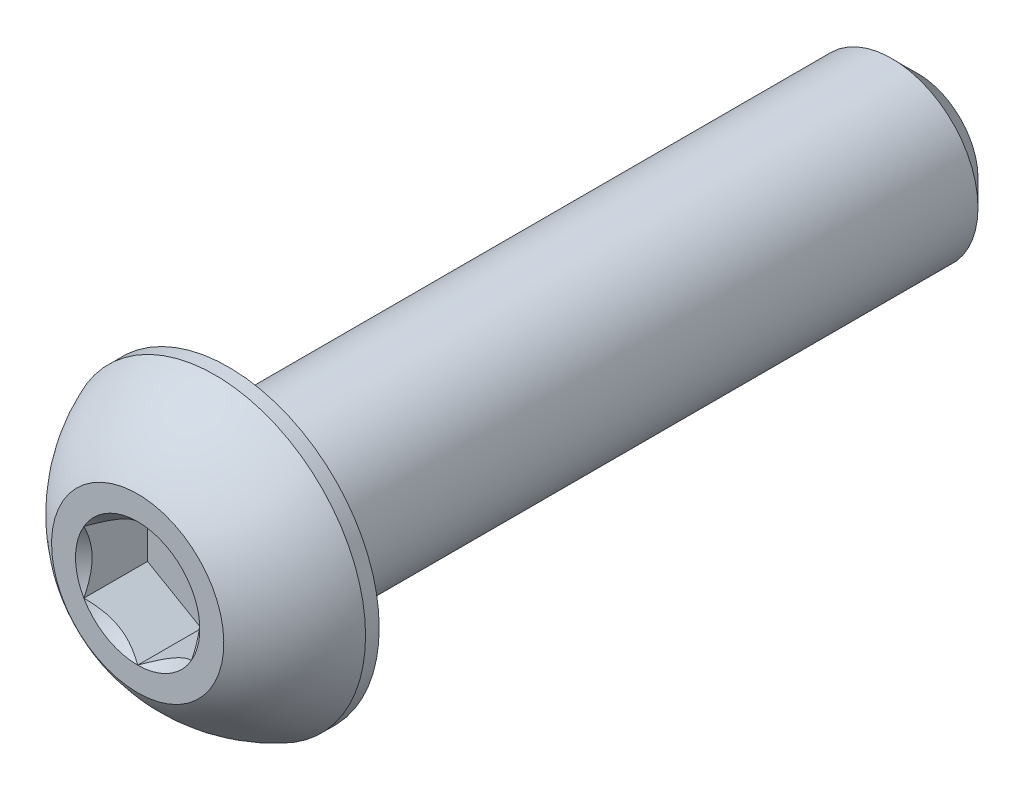
SolidWorks part; units mm, degrees
ref_plane "Front" through (0, 0, 0) normal (0, 0, 1) x (1, 0, 0)
ref_plane "Top" through (0, 0, 0) normal (0, 1, 0) x (1, 0, 0)
ref_plane "Right" through (0, 0, 0) normal (1, 0, 0) x (0, 0, -1)
sketch "Sketch1" plane through (0, 0, 0) normal (1, 0, 0) x (0, 0, -1)
  line L2 (3.3528, 3.175) -> (28.7528, 3.175)
  line L3 (28.7528, 3.175) -> (28.7528, 0)
  line L4 (28.7528, 0) -> (3.3528, 0)
  line L6 (2.8499, 5.5499) -> (3.3528, 5.5499) construction
  line L7 (28.7528, 3.175) -> (28.7528, -3.175) construction
  line L8 (0, 0) -> (3.3528, 0) construction
  line L9 (3.3528, 5.5499) -> (3.3528, -5.5499) construction
  line L11 (3.3528, 3.175) -> (3.3528, 0)
  line L13 (0, 1.9844) -> (0, -1.9844) construction
  line L14 (0, 1.9844) -> (0, 3.175) construction
  arc A3 (0, 3.175) -> (2.8499, 5.5499) centre (5.0603, 0) cw construction
  dimension "D1" = 0.5029
  dimension "Head Ht" = 3.3528
  dimension "Head Dia" = 11.0998
  dimension "Dia" = 6.35
  dimension "Lg" = 25.4
  dimension "Hex" = 3.9688
revolve "Revolve1" add sketch "Sketch1" angle 360 mid plane about L4
chamfer "Chamfer1" distance 0.9525 angle 45 1 edges at (0, 3.175, -28.7528)
sketch "Sketch7" plane through (0, 0, 0) normal (1, 0, 0) x (0, 0, -1)
  line L6 (2.8499, 5.5499) -> (3.3528, 5.5499) construction
  line L8 (0, 0) -> (3.3528, 0) construction
  line L11 (3.3528, 5.5499) -> (3.3528, -5.5499) construction
  line L12 (2.8499, 5.5499) -> (3.3528, 5.5499)
  line L13 (0, 0) -> (3.3528, 0)
  line L14 (0, 1.9844) -> (0, -1.9844) construction
  line L15 (3.3528, 5.5499) -> (3.3528, 0)
  line L16 (0, 3.175) -> (0, 0)
  arc A2 (2.8499, 5.5499) -> (0, 3.175) centre (5.0603, 0) ccw construction
  arc A3 (2.8499, 5.5499) -> (0, 3.175) centre (5.0603, 0) ccw
revolve "Revolve2" add sketch "Sketch7" angle 360 mid plane about L13
sketch "Sketch5" plane through (0, 0, 0) normal (0, 0, 1) x (1, 0, 0)
  line L1 (1.9844, -1.1457) -> (1.9844, 1.1457)
  line L2 (1.9844, 1.1457) -> (0, 2.2914)
  line L3 (0, 2.2914) -> (-1.9844, 1.1457)
  line L4 (-1.9844, 1.1457) -> (-1.9844, -1.1457)
  line L5 (-1.9844, -1.1457) -> (0, -2.2914)
  line L6 (0, -2.2914) -> (1.9844, -1.1457)
  circle A0 centre (0, 0) radius 1.9844 construction
extrude "Cut-Extrude2" cut sketch "Sketch5" against normal blind 2.347
sketch "Sketch6" plane through (0, 0, 0) normal (0, 0, 1) x (1, 0, 0)
  circle A0 centre (0, 0) radius 2.2914
extrude "Cut-Extrude3" cut sketch "Sketch6" against normal blind 2.347 draft 45
